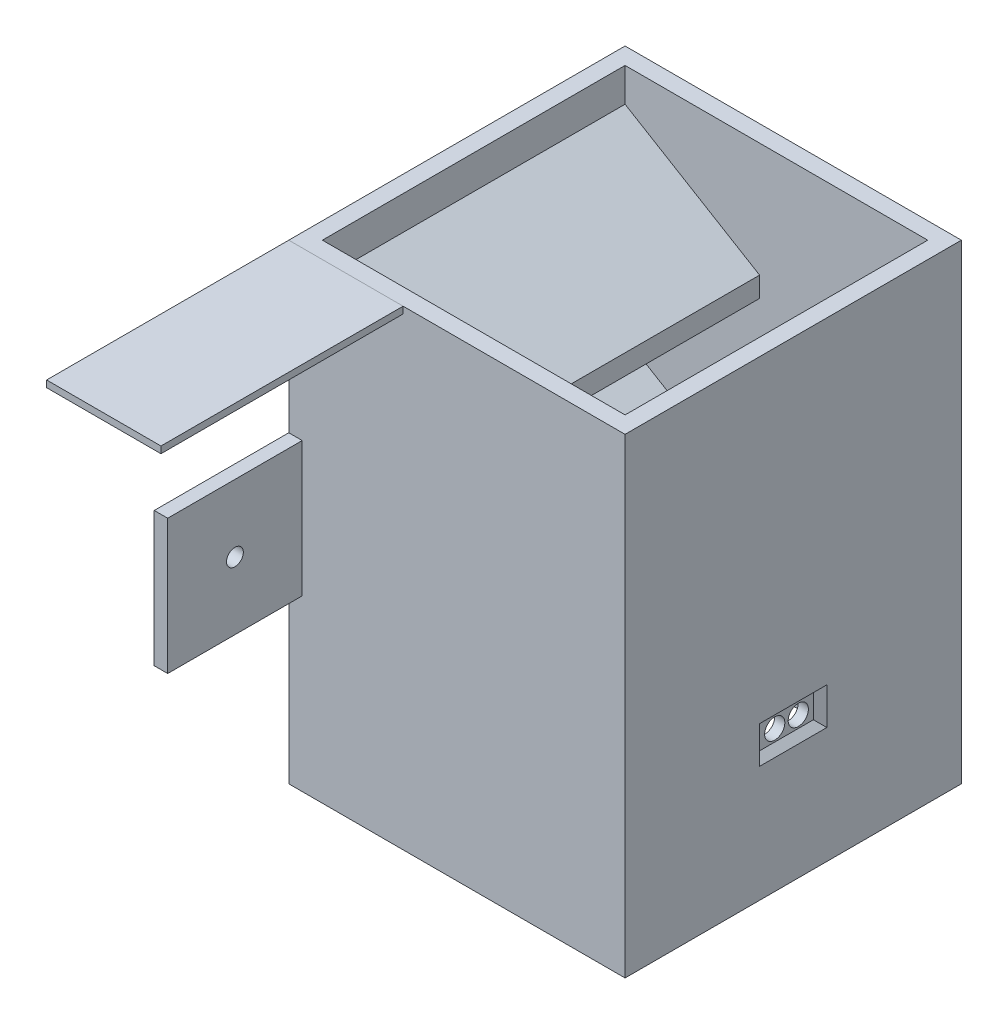
SolidWorks part; units mm, degrees
material "ABS"
ref_plane "Alzado" through (0, 0, 0) normal (0, 0, 1) x (1, 0, 0)
ref_plane "Planta" through (0, 0, 0) normal (0, 1, 0) x (1, 0, 0)
ref_plane "Vista lateral" through (0, 0, 0) normal (1, 0, 0) x (0, 0, -1)
sketch "Croquis2" plane through (0, 0, 0) normal (0, 1, 0) x (1, 0, 0)
  line L0 (-2270.9685, 36.3739) -> (-2220.9685, 36.3739)
  line L1 (-2220.9685, 36.3739) -> (-2220.9685, -13.6261)
  line L2 (-2220.9685, -13.6261) -> (-2270.9685, -13.6261)
  line L3 (-2270.9685, 36.3739) -> (-2270.9685, -13.6261)
  line L4 (-2245.9685, 36.3739) -> (-2245.9685, 33.8739) construction
  line L5 (-2268.4685, 33.8739) -> (-2223.4685, 33.8739)
  line L6 (-2223.4685, 33.8739) -> (-2223.4685, -11.1261)
  line L7 (-2223.4685, -11.1261) -> (-2268.4685, -11.1261)
  line L8 (-2268.4685, -11.1261) -> (-2268.4685, 33.8739)
  point P9 (-2245.9685, 33.8739)
  dimension "D1" = 50
  dimension "D2" = 50
  dimension "D3" = 2.5
  dimension "D4" = 45
  dimension "D5" = 45
extrude "Saliente-Extruir1" add sketch "Croquis2" along normal blind 70
sketch "Croquis3" plane through (0, 0, 11.1261) normal (0, 0, -1) x (-1, 0, 0)
  line L0 (2268.4685, 70) -> (2268.4685, 65) construction
  line L1 (2268.4685, 70) -> (2268.4685, 0) construction
  line L3 (2268.4685, 50) -> (2248.4685, 50)
  line L4 (2248.4685, 50) -> (2248.4685, 65)
  line L5 (2248.4685, 65) -> (2268.4685, 65)
  line L8 (2268.4685, 50) -> (2268.4685, 65)
  dimension "D1" = 5
  dimension "D2" = 15
  dimension "D3" = 20
extrude "Saliente-Extruir2" add sketch "Croquis3" along normal blind 45
sketch "Croquis4" plane through (0, 0, 11.1261) normal (0, 0, -1) x (-1, 0, 0)
  line L0 (2248.4685, 65) -> (2268.4685, 65)
  line L1 (2248.4685, 65) -> (2248.4685, 53)
  line L2 (2248.4685, 65) -> (2248.4685, 50) construction
  line L3 (2248.4685, 53) -> (2268.4685, 65)
  line L4 (2248.4685, 50) -> (2268.4685, 50)
  line L5 (2268.4685, 50) -> (2268.4685, 62)
  line L6 (2268.4685, 62) -> (2248.4685, 50)
  dimension "D1" = 12
  dimension "D2" = 12
extrude "Cortar-Extruir1" cut sketch "Croquis4" along normal blind 45
sketch "Croquis5" plane through (0, 0, 11.1261) normal (0, 0, -1) x (-1, 0, 0)
  line L0 (2248.4685, 50) -> (2223.4685, 50) construction
  line L1 (2223.4685, 70) -> (2223.4685, 0) construction
  line L2 (2223.4685, 50) -> (2223.4685, 35)
  line L3 (2223.4685, 35) -> (2243.4685, 35)
  line L4 (2243.4685, 35) -> (2243.4685, 50)
  line L5 (2243.4685, 50) -> (2223.4685, 50)
  dimension "D1" = 20
extrude "Saliente-Extruir3" add sketch "Croquis5" along normal blind 45
sketch "Croquis6" plane through (0, 0, 11.1261) normal (0, 0, -1) x (-1, 0, 0)
  line L0 (2223.4685, 50) -> (2243.4685, 50)
  line L1 (2243.4685, 50) -> (2243.4685, 38)
  line L2 (2243.4685, 35) -> (2243.4685, 50) construction
  line L3 (2243.4685, 38) -> (2223.4685, 50)
  line L4 (2223.4685, 35) -> (2243.4685, 35)
  line L5 (2243.4685, 35) -> (2223.4685, 47)
  line L6 (2223.4685, 47) -> (2223.4685, 35)
  dimension "D1" = 12
  dimension "D2" = 12
extrude "Cortar-Extruir2" cut sketch "Croquis6" along normal blind 45
sketch "Croquis7" plane through (0, 0, 11.1261) normal (0, 0, -1) x (-1, 0, 0)
  line L0 (2243.4685, 35) -> (2268.4685, 35) construction
  line L1 (2268.4685, 62) -> (2268.4685, 0) construction
  line L2 (2268.4685, 35) -> (2268.4685, 20)
  line L3 (2268.4685, 20) -> (2248.4685, 20)
  line L4 (2248.4685, 20) -> (2248.4685, 35)
  line L5 (2248.4685, 35) -> (2268.4685, 35)
  dimension "D1" = 15
  dimension "D2" = 20
extrude "Saliente-Extruir4" add sketch "Croquis7" along normal blind 45
sketch "Croquis8" plane through (0, 0, 11.1261) normal (0, 0, -1) x (-1, 0, 0)
  line L2 (2248.4685, 35) -> (2268.4685, 35)
  line L3 (2268.4685, 20) -> (2248.4685, 20)
  line L7 (2268.4685, 20) -> (2268.4685, 32)
  line L8 (2268.4685, 32) -> (2248.4685, 20)
  line L9 (2248.4685, 35) -> (2248.4685, 23)
  line L10 (2248.4685, 35) -> (2248.4685, 20) construction
  line L11 (2248.4685, 23) -> (2268.4685, 35)
  dimension "D1" = 12
  dimension "D2" = 12
extrude "Cortar-Extruir3" cut sketch "Croquis8" along normal blind 45
sketch "Croquis10" plane through (0, 70, 0) normal (0, 1, 0) x (1, 0, 0)
  line L11 (-2270.9685, -13.6261) -> (-2270.9685, -49.6261)
  line L12 (-2270.9685, -178.6261) -> (-2270.9685, 61.3739) construction
  line L13 (-2270.9685, -49.6261) -> (-2253.9685, -49.6261)
  line L14 (-2253.9685, -49.6261) -> (-2253.9685, -13.6261)
  line L15 (-2270.9685, -13.6261) -> (-2220.9685, -13.6261) construction
  line L16 (-2253.9685, -13.6261) -> (-2270.9685, -13.6261)
  dimension "D1" = 17
  dimension "D2" = 36
extrude "Saliente-Extruir6" add sketch "Croquis10" against normal blind 1 separate body
sketch "Croquis12" plane through (-2270.9685, 0, 0) normal (-1, 0, 0) x (0, 0, 1)
  line L0 (-36.3739, 25.2013) -> (-36.3739, 45.2013)
  line L1 (-36.3739, 70) -> (-36.3739, 0) construction
  line L2 (-36.3739, 45.2013) -> (-56.3739, 45.2013)
  line L3 (-56.3739, 45.2013) -> (-56.3739, 25.2013)
  line L4 (-56.3739, 25.2013) -> (-36.3739, 25.2013)
  line L5 (13.6261, 45.2013) -> (33.6261, 45.2013)
  line L6 (13.6261, 70) -> (13.6261, 0) construction
  line L7 (33.6261, 45.2013) -> (33.6261, 25.2013)
  line L8 (33.6261, 25.2013) -> (13.6261, 25.2013)
  line L9 (13.6261, 25.2013) -> (13.6261, 45.2013)
  line L10 (-56.3739, 25.2013) -> (-36.3739, 45.2013) construction
  line L11 (13.6261, 45.2013) -> (33.6261, 25.2013) construction
  circle A0 centre (-46.3739, 35.2013) radius 1.25
  circle A1 centre (23.6261, 35.2013) radius 1.25
  point P5 (-36.3739, 35.2013)
  dimension "D5" = 2.5
  dimension "D6" = 2.5
  dimension "D1" = 20
  dimension "D2" = 20
  dimension "D3" = 20
  dimension "D4" = 20
extrude "Saliente-Extruir7" add sketch "Croquis12" against normal blind 2
sketch "Croquis13" plane through (-2220.9685, 0, 0) normal (1, 0, 0) x (0, 0, -1)
  line L0 (11.3739, 0) -> (11.3739, 20) construction
  line L1 (-13.6261, 0) -> (36.3739, 0) construction
  line L2 (16.3739, 20) -> (6.3739, 20) construction
  line L3 (6.3739, 22.75) -> (6.3739, 17.25)
  line L4 (6.3739, 22.75) -> (16.3739, 22.75)
  line L5 (16.3739, 22.75) -> (16.3739, 17.25)
  line L6 (16.3739, 17.25) -> (6.3739, 17.25)
  point P7 (11.3739, 20)
  point P10 (6.3739, 20)
  dimension "D1" = 20
  dimension "D2" = 10
  dimension "D3" = 5.5
extrude "Cortar-Extruir4" cut sketch "Croquis13" against normal blind 1 draft 45
sketch "Croquis14" plane through (-2220.9685, 0, 0) normal (1, 0, 0) x (0, 0, -1)
  line L0 (11.3739, 0) -> (11.3739, 20) construction
  line L1 (-13.6261, 0) -> (36.3739, 0) construction
  line L2 (11.1239, 20) -> (11.6239, 20) construction
  line L3 (11.6239, 20) -> (13.1239, 20) construction
  line L4 (11.1239, 20) -> (9.6239, 20) construction
  circle A0 centre (9.6239, 20) radius 1.5
  circle A1 centre (13.1239, 20) radius 1.5
  point P7 (11.3739, 20)
  dimension "D1" = 20
  dimension "D2" = 0.5
  dimension "D3" = 1.5
  dimension "D4" = 1.5
extrude "Cortar-Extruir5" cut sketch "Croquis14" against normal up to surface (2.5 mm away) up to face at (-2223.4685, 60, -11.3739)
